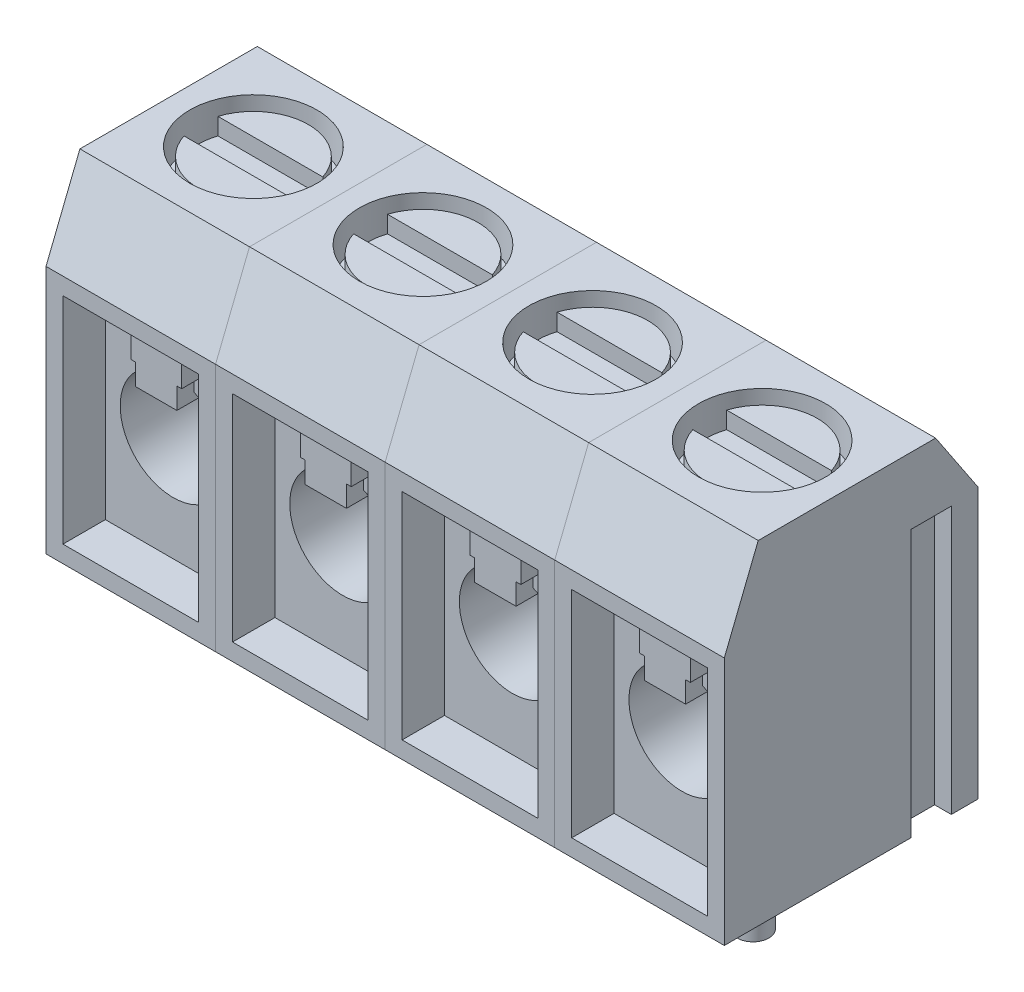
SolidWorks part; units mm, degrees
ref_plane "Front Plane" through (0, 0, 0) normal (0, 0, 1) x (1, 0, 0)
ref_plane "Top Plane" through (0, 0, 0) normal (0, 1, 0) x (1, 0, 0)
ref_plane "Right Plane" through (0, 0, 0) normal (1, 0, 0) x (0, 0, -1)
sketch "Sketch1" plane through (0, 0, 0) normal (0, 1, 0) x (1, 0, 0)
  line L1 (-2.54, -3.8) -> (2.54, -3.8)
  line L2 (-2.54, -3.8) -> (-2.54, 3.8)
  line L3 (-2.54, 3.8) -> (2.54, 3.8)
  line L4 (2.54, -3.8) -> (2.54, 3.8)
  line L5 (-2.54, -3.8) -> (2.54, 3.8) construction
  line L6 (-2.54, 3.8) -> (2.54, -3.8) construction
  point P0 (0, 0)
  dimension "D1" = 7.6
  dimension "D2" = 5.08
extrude "Boss-Extrude1" add sketch "Sketch1" along normal blind 10
sketch "Sketch2" plane through (2.54, 0, 0) normal (1, 0, 0) x (0, 0, -1)
  line L0 (-2.784, 10) -> (-3.8, 10)
  line L1 (-3.8, 10) -> (3.8, 10) construction
  line L2 (-3.8, 10) -> (-3.8, 7.46)
  line L3 (-3.8, 10) -> (-3.8, 0) construction
  line L4 (-3.8, 7.46) -> (-2.784, 10)
  line L5 (2.53, 10) -> (3.8, 10)
  line L6 (3.8, 10) -> (3.8, 8.095)
  line L7 (3.8, 10) -> (3.8, 0) construction
  line L8 (3.8, 8.095) -> (2.53, 10)
  dimension "D1" = 1.27
  dimension "D2" = 1.905
  dimension "D3" = 1.016
  dimension "D4" = 2.54
extrude "Cut-Extrude1" cut sketch "Sketch2" against normal through all
sketch "Sketch3" plane through (0, 10, 0) normal (0, 1, 0) x (1, 0, 0)
  line L0 (-2.54, -0.127) -> (2.54, -0.127) construction
  line L1 (-2.54, 2.53) -> (-2.54, -2.784) construction
  line L2 (2.54, -2.784) -> (2.54, 2.53) construction
  circle A0 centre (0, -0.127) radius 1.905
  dimension "D1" = 3.81
extrude "Cut-Extrude2" cut sketch "Sketch3" against normal blind 1.016
sketch "Sketch10" plane through (0, 8.984, 0) normal (0, 1, 0) x (1, 0, 0)
  circle A0 centre (0, -0.127) radius 1.651
  circle A1 centre (0, -0.127) radius 1.905 construction
  dimension "D1" = 0.254
extrude "Boss-Extrude6" add sketch "Sketch10" along normal offset from surface (0.762 mm away) 0.254 up to face at (0, 10, 2.032)
sketch "Sketch11" plane through (0, 9.746, 0) normal (0, 1, 0) x (1, 0, 0)
  line L1 (-1.651, -0.635) -> (1.651, -0.635)
  line L2 (-1.651, -0.635) -> (-1.651, 0.381)
  line L3 (-1.651, 0.381) -> (1.651, 0.381)
  line L4 (1.651, -0.635) -> (1.651, 0.381)
  line L5 (-1.651, -0.635) -> (1.651, 0.381) construction
  line L6 (-1.651, 0.381) -> (1.651, -0.635) construction
  circle A0 centre (0, -0.127) radius 1.651 construction
  circle A1 centre (0, -0.127) radius 1.651 construction
  point P0 (0, -0.127)
  dimension "D1" = 1.016
extrude "Cut-Extrude5" cut sketch "Sketch11" against normal blind 0.508
sketch "Sketch4" plane through (0, 0, 3.8) normal (0, 0, 1) x (1, 0, 0)
  line L0 (0, 0) -> (0, 3.73) construction
  line L1 (-2.032, 0.508) -> (2.032, 0.508)
  line L2 (-2.032, 0.508) -> (-2.032, 6.952)
  line L3 (-2.032, 6.952) -> (2.032, 6.952)
  line L4 (2.032, 0.508) -> (2.032, 6.952)
  line L5 (-2.032, 0.508) -> (2.032, 6.952) construction
  line L6 (-2.032, 6.952) -> (2.032, 0.508) construction
  line L7 (-2.54, 0) -> (2.54, 0) construction
  line L8 (2.54, 7.46) -> (2.54, 0) construction
  line L9 (-2.54, 7.46) -> (2.54, 7.46) construction
  point P0 (0, 3.73)
  dimension "D1" = 0.508
  dimension "D2" = 0.508
  dimension "D3" = 0.508
extrude "Cut-Extrude3" cut sketch "Sketch4" against normal offset from surface (6.33 mm away) 1.27 up to face at (0, 4.0475, -3.8)
sketch "Sketch5" plane through (0, 0, -2.53) normal (0, 0, 1) x (1, 0, 0)
  line L0 (2.032, 6.952) -> (-2.032, 6.952) construction
  line L1 (-2.032, 6.444) -> (2.032, 6.444)
  line L2 (-2.032, 6.444) -> (-2.032, 0.508)
  line L3 (-2.032, 0.508) -> (2.032, 0.508)
  line L4 (2.032, 6.444) -> (2.032, 0.508)
  line L5 (-2.032, 6.444) -> (2.032, 0.508) construction
  line L6 (-2.032, 0.508) -> (2.032, 6.444) construction
  line L7 (-2.032, 6.952) -> (-2.032, 0.508) construction
  point P0 (0, 3.476)
  dimension "D1" = 0.508
extrude "Boss-Extrude2" add sketch "Sketch5" along normal offset from surface (5.06 mm away) 1.27 up to face at (0, 3.73, 3.8)
sketch "Sketch6" plane through (0, 0, 2.53) normal (0, 0, 1) x (1, 0, 0)
  line L0 (0, 0.508) -> (0, 3.683) construction
  line L1 (2.032, 0.508) -> (-2.032, 0.508) construction
  circle A0 centre (0, 3.683) radius 1.5875
  dimension "D1" = 3.175
  dimension "D2" = 3.175
extrude "Cut-Extrude4" cut sketch "Sketch6" against normal blind 5.08
sketch "Sketch7" plane through (0, 0, 2.53) normal (0, 0, 1) x (1, 0, 0)
  line L0 (-2.032, 6.952) -> (2.032, 6.952) construction
  line L1 (-0.6186, 6.952) -> (0.6186, 6.952)
  line L2 (-0.6186, 6.952) -> (-0.6186, 4.92)
  line L3 (-0.6186, 4.92) -> (0.6186, 4.92)
  line L4 (0.6186, 6.952) -> (0.6186, 4.92)
  line L5 (-0.6186, 6.952) -> (0.6186, 4.92) construction
  line L6 (-0.6186, 4.92) -> (0.6186, 6.952) construction
  line L7 (0, 3.683) -> (0, 4.92) construction
  point P0 (0, 5.936)
  dimension "D1" = 1.2373
  dimension "D2" = 2.032
extrude "Boss-Extrude3" add sketch "Sketch7" against normal up to surface (5.06 mm away) and the other way blind 0.508 up to face at (0, 6.698, -2.53)
sketch "Sketch8" plane through (0, 0, 3.038) normal (0, 0, 1) x (1, 0, 0)
  line L0 (0.6186, 5.936) -> (-0.6186, 5.936) construction
  line L1 (0.6186, 4.92) -> (0.6186, 6.952) construction
  line L2 (-0.6186, 6.952) -> (-0.6186, 4.92) construction
  line L4 (-0.762, 5.555) -> (0.762, 5.555)
  line L5 (-0.762, 5.555) -> (-0.762, 6.317)
  line L6 (-0.762, 6.317) -> (0.762, 6.317)
  line L7 (0.762, 5.555) -> (0.762, 6.317)
  line L8 (-0.762, 5.555) -> (0.762, 6.317) construction
  line L9 (-0.762, 6.317) -> (0.762, 5.555) construction
  point P6 (0, 5.936)
  dimension "D1" = 0.762
  dimension "D2" = 1.524
extrude "Boss-Extrude4" add sketch "Sketch8" against normal up to surface (0.508 mm away) up to face at (0, 4.2541, 2.53)
sketch "Sketch9" plane through (0, 0, 0) normal (0, -1, 0) x (1, 0, 0)
  line L0 (0, 0) -> (0, 0.4) construction
  line L1 (2.54, -3.8) -> (-2.54, -3.8) construction
  circle A0 centre (0, 0.4) radius 0.475
  dimension "D1" = 0.95
  dimension "D2" = 4.2
extrude "Boss-Extrude5" add sketch "Sketch9" along normal blind 2.54
sketch "Sketch15" plane through (-2.54, 0, 0) normal (-1, 0, 0) x (0, 0, 1)
  line L0 (-3.8, 0) -> (3.8, 0) construction
  line L1 (-3, 8) -> (-1.8, 8)
  line L2 (-3, 8) -> (-3, 0)
  line L3 (-3, 0) -> (-1.8, 0)
  line L4 (-1.8, 8) -> (-1.8, 0)
  line L5 (-3, 8) -> (-1.8, 0) construction
  line L6 (-3, 0) -> (-1.8, 8) construction
  line L7 (-3.8, 8.095) -> (-3.8, 0) construction
  point P0 (-2.4, 4)
  dimension "D1" = 8
  dimension "D2" = 1.2
  dimension "D3" = 0.8
extrude "Boss-Extrude8" add sketch "Sketch15" along normal blind 0.5
sketch "Sketch16" plane through (0, 0, 0) normal (0, -1, 0) x (1, 0, 0)
  line L0 (-3.04, -1.8) -> (-2.54, -1.8) construction
  line L1 (2.04, -1.8) -> (2.54, -1.8)
  line L2 (2.04, -1.8) -> (2.04, -3)
  line L3 (2.04, -3) -> (2.54, -3)
  line L4 (2.54, -1.8) -> (2.54, -3)
  line L5 (2.04, -1.8) -> (2.54, -3) construction
  line L6 (2.04, -3) -> (2.54, -1.8) construction
  line L7 (2.54, 3.8) -> (2.54, -3.8) construction
  line L8 (-3.04, -3) -> (-3.04, -1.8) construction
  point P0 (2.29, -2.4)
extrude "Cut-Extrude7" cut sketch "Sketch16" against normal up to surface (8 mm away) up to face at (-2.79, 8, -2.4)
pattern_linear "LPattern1" count 4 spacing 5.08 along (-1, 0, 0) of bodies 118 108
